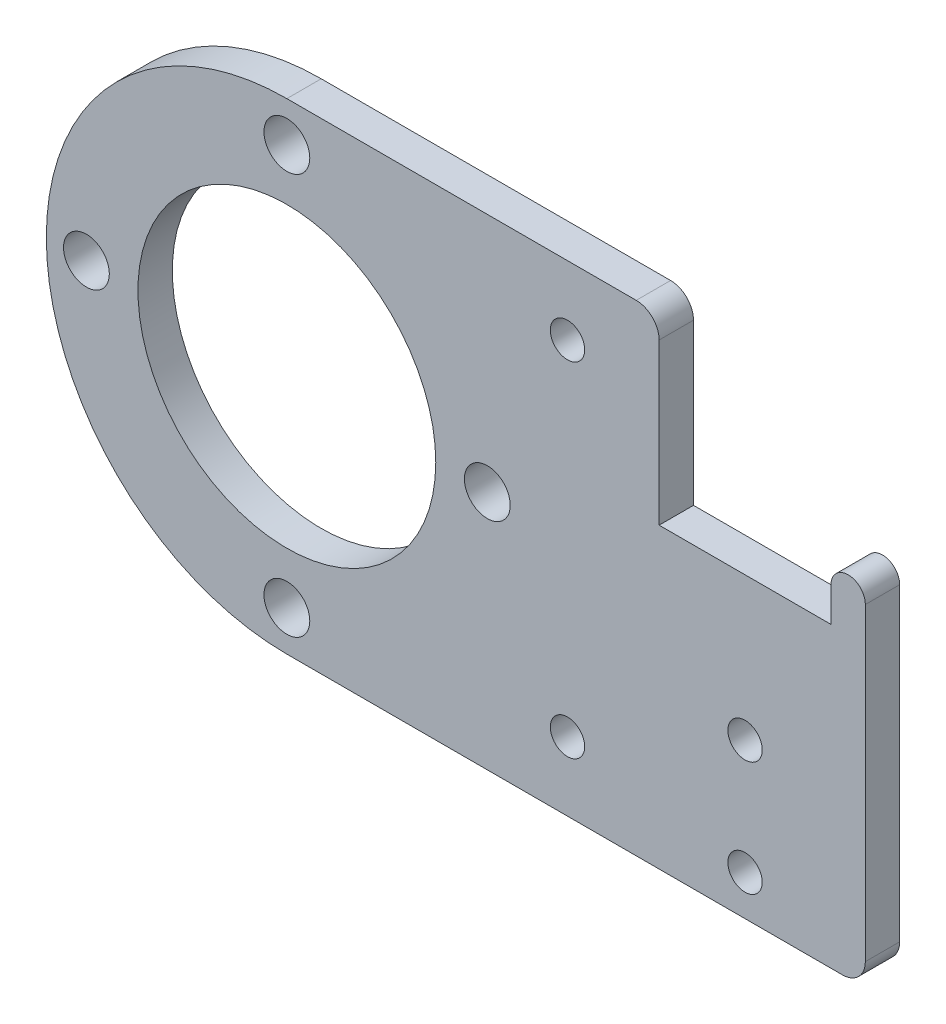
SolidWorks part; units mm, degrees
material "Thornel Mat VMA"
ref_plane "前视基准面" through (0, 0, 0) normal (0, 0, 1) x (1, 0, 0)
ref_plane "上视基准面" through (0, 0, 0) normal (0, 1, 0) x (1, 0, 0)
ref_plane "右视基准面" through (0, 0, 0) normal (1, 0, 0) x (0, 0, -1)
sketch "草图1" plane through (0, 0, 0) normal (0, 0, 1) x (1, 0, 0)
  line L0 (0, 21) -> (32.5, 21)
  line L1 (32.5, 21) -> (32.5, 5)
  line L2 (32.5, 5) -> (47.5, 5)
  line L3 (50.5, 8) -> (50.5, -21)
  line L4 (50.5, -21) -> (0, -21)
  line L5 (40, 5) -> (40, -21) construction
  line L6 (24.5, 15) -> (24.5, -15) construction
  line L7 (47.5, 5) -> (47.5, 8)
  circle A0 centre (0, 0) radius 13
  circle A1 centre (0, 0) radius 17.5 construction
  arc A2 (0, 21) -> (0, -21) centre (0, 0) ccw
  circle A3 centre (17.5, 0) radius 2
  circle A4 centre (0, -17.5) radius 2
  circle A5 centre (-17.5, 0) radius 2
  circle A6 centre (0, 17.5) radius 2
  circle A7 centre (40, -7.5) radius 1.5
  circle A8 centre (40, -17.5) radius 1.5
  circle A9 centre (24.5, 15) radius 1.5
  circle A10 centre (24.5, -15) radius 1.5
  arc A11 (47.5, 8) -> (50.5, 8) centre (49, 8) cw
  point P21 (0, 0)
  point P27 (24.5, 0)
  dimension "D1" = 26
  dimension "D2" = 35
  dimension "D3" = 21
  dimension "D4" = 4
  dimension "D8" = 12.5
  dimension "D9" = 10
  dimension "D10" = 3
  dimension "D14" = 3
  dimension "D16" = 1.5
  dimension "D6" = 5
  dimension "D7" = 32.5
  dimension "D11" = 7.5
  dimension "D12" = 15
  dimension "D13" = 8
  dimension "D15" = 30
  dimension "D17" = 3
  dimension "D5" = 4
extrude "凸台-拉伸1" add sketch "草图1" along normal blind 3
fillet "圆角1" radius 2 2 edges at (50.5, -21, 1.5) (32.5, 21, 1.5)
